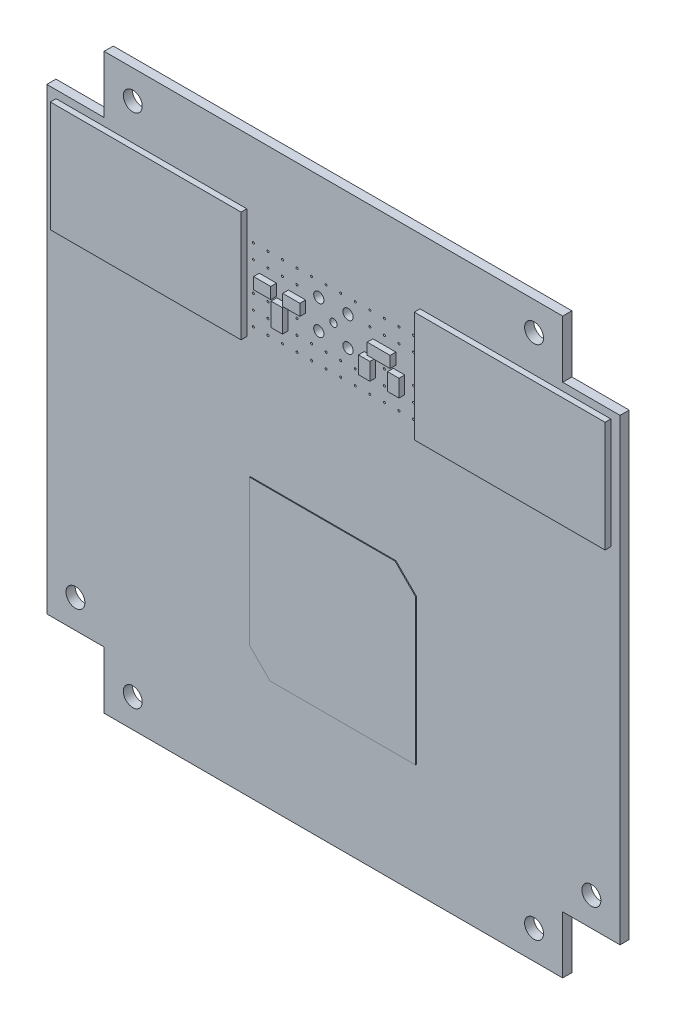
SolidWorks part; units mm, degrees
ref_plane "Front Plane" through (0, 0, 0) normal (0, 0, 1) x (1, 0, 0)
ref_plane "Top Plane" through (0, 0, 0) normal (0, 1, 0) x (1, 0, 0)
ref_plane "Right Plane" through (0, 0, 0) normal (1, 0, 0) x (0, 0, -1)
sketch "Sketch1" plane through (0, 0, 0) normal (0, 0, 1) x (1, 0, 0)
  line L0 (-40, 21) -> (40, 21)
  line L1 (40, 21) -> (40, 11)
  line L2 (40, 11) -> (50, 11)
  line L3 (50, 11) -> (50, -69)
  line L4 (50, -69) -> (40, -69)
  line L5 (40, -69) -> (40, -79)
  line L6 (40, -79) -> (-40, -79)
  line L7 (-40, -79) -> (-40, -69)
  line L8 (-40, -69) -> (-50, -69)
  line L9 (-50, -69) -> (-50, 11)
  line L10 (-50, 11) -> (-40, 11)
  line L11 (-40, 11) -> (-40, 21)
extrude "BOARD" add sketch "Sketch1" along normal blind 1.6 separate body
sketch "Sketch2" plane through (0, 0, 0) normal (0, 0, 1) x (1, 0, 0)
  circle A0 centre (-35, -74) radius 1.65
  circle A1 centre (35, -74) radius 1.65
  circle A2 centre (-35, 16) radius 1.65
  circle A3 centre (35, 16) radius 1.65
  circle A4 centre (-45, -64) radius 1.65
  circle A5 centre (45, -64) radius 1.65
  circle A6 centre (24.13, 0) radius 1.7145
  circle A7 centre (39.37, 0) radius 1.7145
  circle A8 centre (-39.37, 0) radius 1.7145
  circle A9 centre (-24.13, 0) radius 1.7145
  circle A10 centre (-11.43, -2.54) radius 0.175
  circle A11 centre (-13.97, -2.54) radius 0.175
  circle A12 centre (-13.97, 2.54) radius 0.175
  circle A13 centre (-11.43, 2.54) radius 0.175
  circle A14 centre (-8.89, 2.54) radius 0.175
  circle A15 centre (-6.35, 2.54) radius 0.175
  circle A16 centre (13.97, 2.54) radius 0.175
  circle A17 centre (11.43, 2.54) radius 0.175
  circle A18 centre (8.89, 2.54) radius 0.175
  circle A19 centre (6.35, 2.54) radius 0.175
  circle A20 centre (-6.35, 5.08) radius 0.175
  circle A21 centre (-3.81, 5.08) radius 0.175
  circle A22 centre (-1.27, 5.08) radius 0.175
  circle A23 centre (1.27, 5.08) radius 0.175
  circle A24 centre (3.81, 5.08) radius 0.175
  circle A25 centre (6.35, 5.08) radius 0.175
  circle A26 centre (-6.35, -2.54) radius 0.175
  circle A27 centre (-6.35, -5.08) radius 0.175
  circle A28 centre (-3.81, -5.08) radius 0.175
  circle A29 centre (-1.27, -5.08) radius 0.175
  circle A30 centre (1.27, -5.08) radius 0.175
  circle A31 centre (3.81, -5.08) radius 0.175
  circle A32 centre (3.81, -7.62) radius 0.175
  circle A33 centre (-6.35, -7.62) radius 0.175
  circle A34 centre (-8.89, -7.62) radius 0.175
  circle A35 centre (-11.43, -7.62) radius 0.175
  circle A36 centre (-11.43, -5.08) radius 0.175
  circle A37 centre (6.35, -7.62) radius 0.175
  circle A38 centre (8.89, -7.62) radius 0.175
  circle A39 centre (8.89, -5.08) radius 0.175
  circle A40 centre (8.89, -2.54) radius 0.175
  circle A41 centre (11.43, -7.62) radius 0.175
  circle A42 centre (13.97, -7.62) radius 0.175
  circle A43 centre (13.97, -5.08) radius 0.175
  circle A44 centre (13.97, -2.54) radius 0.175
  circle A45 centre (-3.81, -7.62) radius 0.175
  circle A46 centre (-1.27, -7.62) radius 0.175
  circle A47 centre (1.27, -7.62) radius 0.175
  circle A48 centre (-13.97, -5.08) radius 0.175
  circle A49 centre (-13.97, -7.62) radius 0.175
  circle A50 centre (-8.89, 5.08) radius 0.175
  circle A51 centre (-11.43, 5.08) radius 0.175
  circle A52 centre (-13.97, 5.08) radius 0.175
  circle A53 centre (8.89, 5.08) radius 0.175
  circle A54 centre (11.43, 5.08) radius 0.175
  circle A55 centre (13.97, 5.08) radius 0.175
extrude "NON-PLATED HOLES" cut sketch "Sketch2" along normal through all
sketch "Sketch3" plane through (0, 0, 0) normal (0, 0, 1) x (1, 0, 0)
  circle A0 centre (0, -49.85) radius 0.76
  circle A1 centre (0, 0) radius 0.635
  circle A2 centre (2.55, 2.55) radius 0.89
  circle A3 centre (-2.55, 2.55) radius 0.89
  circle A4 centre (-2.55, -2.55) radius 0.89
  circle A5 centre (2.55, -2.55) radius 0.89
extrude "PLATED HOLES" cut sketch "Sketch3" along normal through all
ref_plane "Plane1" through (0, 0, 1.6) normal (0, 0, 1) x (1, 0, 0)
sketch "Sketch4" plane through (0, 0, 1.6) normal (0, 0, 1) x (1, 0, 0)
  line L0 (7.3584, -1.6766) -> (7.3584, -4.6734)
  line L1 (7.3584, -4.6734) -> (5.367, -4.6734)
  line L2 (5.367, -4.6734) -> (5.367, -1.6766)
  line L3 (5.367, -1.6766) -> (7.3584, -1.6766)
extrude "C1608-1" add sketch "Sketch4" along normal blind 1 separate body
sketch "Sketch5" plane through (0, 0, 1.6) normal (0, 0, 1) x (1, 0, 0)
  line L0 (12.4384, -1.6766) -> (12.4384, -4.6734)
  line L1 (12.4384, -4.6734) -> (10.447, -4.6734)
  line L2 (10.447, -4.6734) -> (10.447, -1.6766)
  line L3 (10.447, -1.6766) -> (12.4384, -1.6766)
extrude "C1608-2" add sketch "Sketch5" along normal blind 1 separate body
sketch "Sketch6" plane through (0, 0, 1.6) normal (0, 0, 1) x (1, 0, 0)
  line L0 (-7.8484, 1.0084) -> (-4.8516, 1.0084)
  line L1 (-4.8516, 1.0084) -> (-4.8516, -0.983)
  line L2 (-4.8516, -0.983) -> (-7.8484, -0.983)
  line L3 (-7.8484, -0.983) -> (-7.8484, 1.0084)
extrude "C1608-3" add sketch "Sketch6" along normal blind 1 separate body
sketch "Sketch7" plane through (0, 0, 1.6) normal (0, 0, 1) x (1, 0, 0)
  line L0 (-12.9284, 1.0084) -> (-9.9316, 1.0084)
  line L1 (-9.9316, 1.0084) -> (-9.9316, -0.983)
  line L2 (-9.9316, -0.983) -> (-12.9284, -0.983)
  line L3 (-12.9284, -0.983) -> (-12.9284, 1.0084)
extrude "C1608-4" add sketch "Sketch7" along normal blind 1 separate body
sketch "Sketch8" plane through (0, 0, 1.6) normal (0, 0, 1) x (1, 0, 0)
  line L0 (6.8916, 1.0084) -> (10.8884, 1.0084)
  line L1 (10.8884, 1.0084) -> (10.8884, -0.983)
  line L2 (10.8884, -0.983) -> (6.8916, -0.983)
  line L3 (6.8916, -0.983) -> (6.8916, 1.0084)
extrude "L2012C-1" add sketch "Sketch8" along normal blind 1 separate body
sketch "Sketch9" plane through (0, 0, 1.6) normal (0, 0, 1) x (1, 0, 0)
  line L0 (-7.8816, -1.1766) -> (-7.8816, -5.1734)
  line L1 (-7.8816, -5.1734) -> (-9.873, -5.1734)
  line L2 (-9.873, -5.1734) -> (-9.873, -1.1766)
  line L3 (-9.873, -1.1766) -> (-7.8816, -1.1766)
extrude "L2012C-2" add sketch "Sketch9" along normal blind 1 separate body
sketch "Sketch10" plane through (0, 0, 1.6) normal (0, 0, 1) x (1, 0, 0)
  line L0 (15.113, 9.652) -> (48.387, 9.652)
  line L1 (48.387, 9.652) -> (48.387, -9.652)
  line L2 (48.387, -9.652) -> (15.113, -9.652)
  line L3 (15.113, -9.652) -> (15.113, 9.652)
extrude "CMMOUNTPAD2-1" add sketch "Sketch10" along normal blind 1 separate body
sketch "Sketch11" plane through (0, 0, 1.6) normal (0, 0, 1) x (1, 0, 0)
  line L0 (-48.387, 9.652) -> (-15.113, 9.652)
  line L1 (-15.113, 9.652) -> (-15.113, -9.652)
  line L2 (-15.113, -9.652) -> (-48.387, -9.652)
  line L3 (-48.387, -9.652) -> (-48.387, 9.652)
extrude "CMMOUNTPAD2-2" add sketch "Sketch11" along normal blind 1 separate body
sketch "Sketch12" plane through (0, 0, 0) normal (0, 0, 1) x (1, 0, 0)
  line L0 (6.985, -42.8015) -> (-7.0485, -42.8015)
  line L1 (-7.0485, -42.8015) -> (-7.0485, -56.835)
  line L2 (-7.0485, -56.835) -> (6.985, -56.835)
  line L3 (6.985, -56.835) -> (6.985, -42.8015)
extrude "PANELSMA-1" add sketch "Sketch12" against normal blind 1 separate body
sketch "Sketch13" plane through (0, 0, 0) normal (0, 0, 1) x (1, 0, 0)
  line L0 (3.3015, 3.3016) -> (-3.3015, 3.3016)
  line L1 (-3.3015, 3.3016) -> (-3.3015, -3.3015)
  line L2 (-3.3015, -3.3015) -> (3.3015, -3.3015)
  line L3 (3.3015, -3.3015) -> (3.3015, 3.3016)
extrude "BU-SMA-V-1" add sketch "Sketch13" against normal blind 1 separate body
sketch "Sketch14" plane through (0, 0, 1.6) normal (0, 0, 1) x (1, 0, 0)
  line L0 (-14.5, -49.85) -> (14.5, -49.85) construction
  line L1 (0, -1.98) -> (0, 1.98) construction
  line L2 (0, -49.85) -> (0, -59.5) construction
  line L3 (0, -49.85) -> (0, -30.5) construction
  line L4 (0, -30.5) -> (10.9, -30.5)
  line L5 (14.5, -49.85) -> (14.5, -34.1)
  line L6 (10.9, -30.5) -> (14.5, -34.1)
  line L7 (0, -59.5) -> (14.5, -59.5)
  line L8 (14.5, -59.5) -> (14.5, -49.85)
  line L9 (0, -30.5) -> (-14.5, -30.5)
  line L10 (-14.5, -30.5) -> (-14.5, -49.85)
  line L11 (-14.5, -49.85) -> (-14.5, -55.9)
  line L12 (0, -59.5) -> (-10.9, -59.5)
  line L13 (-14.5, -55.9) -> (-10.9, -59.5)
  point P6 (0, -49.85)
  point P10 (0, -49.85)
extrude "Boss-Extrude12" add sketch "Sketch14" along normal blind 0.15
sketch "Sketch15" plane through (0, 0, 1.6) normal (0, 0, 1) x (1, 0, 0)
  line L0 (0, 0) -> (-15.113, 0) construction
  line L1 (-15.113, -9.652) -> (-15.113, 9.652) construction
  line L2 (-15.113, 0) -> (-15.113, 9.652) construction
  dimension "D1" = 15.113
  dimension "D2" = 9.652
